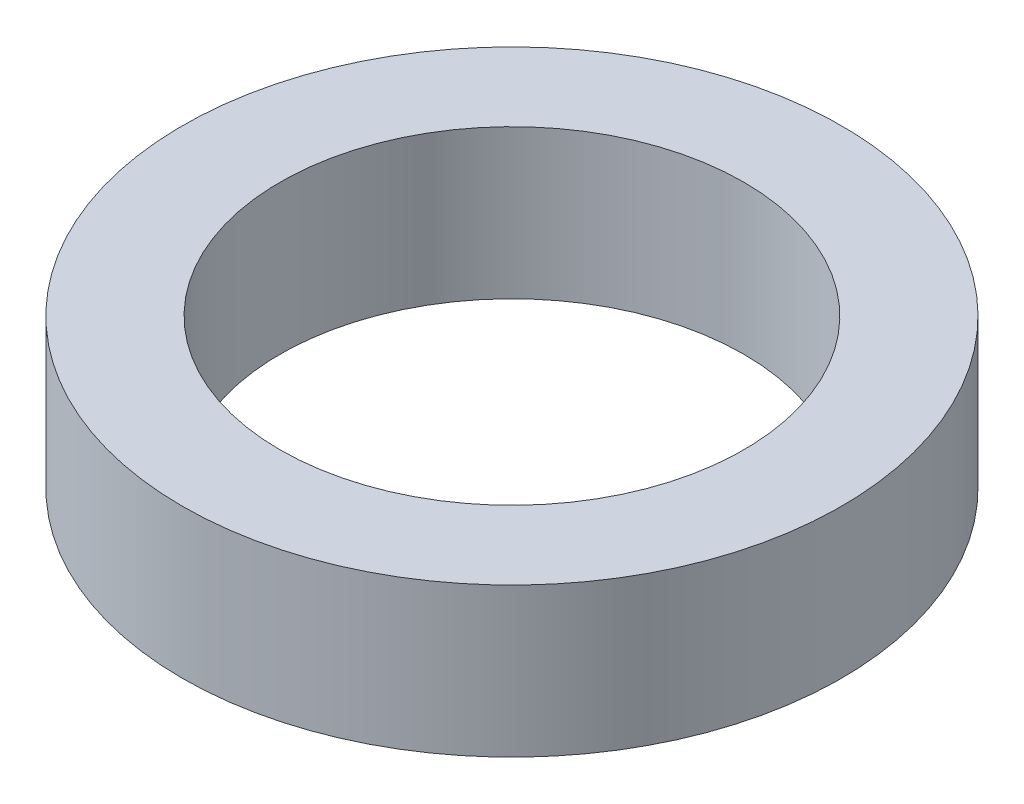
SolidWorks part; units mm, degrees
ref_plane "Front Plane" through (0, 0, 0) normal (0, 0, 1) x (1, 0, 0)
ref_plane "Top Plane" through (0, 0, 0) normal (0, 1, 0) x (1, 0, 0)
ref_plane "Right Plane" through (0, 0, 0) normal (1, 0, 0) x (0, 0, -1)
sketch "Sketch1" plane through (0, 0, 0) normal (0, 1, 0) x (1, 0, 0)
  circle A0 centre (0, 0) radius 3.5
  circle A1 centre (0, 0) radius 4.975
  dimension "D1" = 7
  dimension "D2" = 9.95
extrude "Boss-Extrude1" add sketch "Sketch1" along normal blind 2.25
